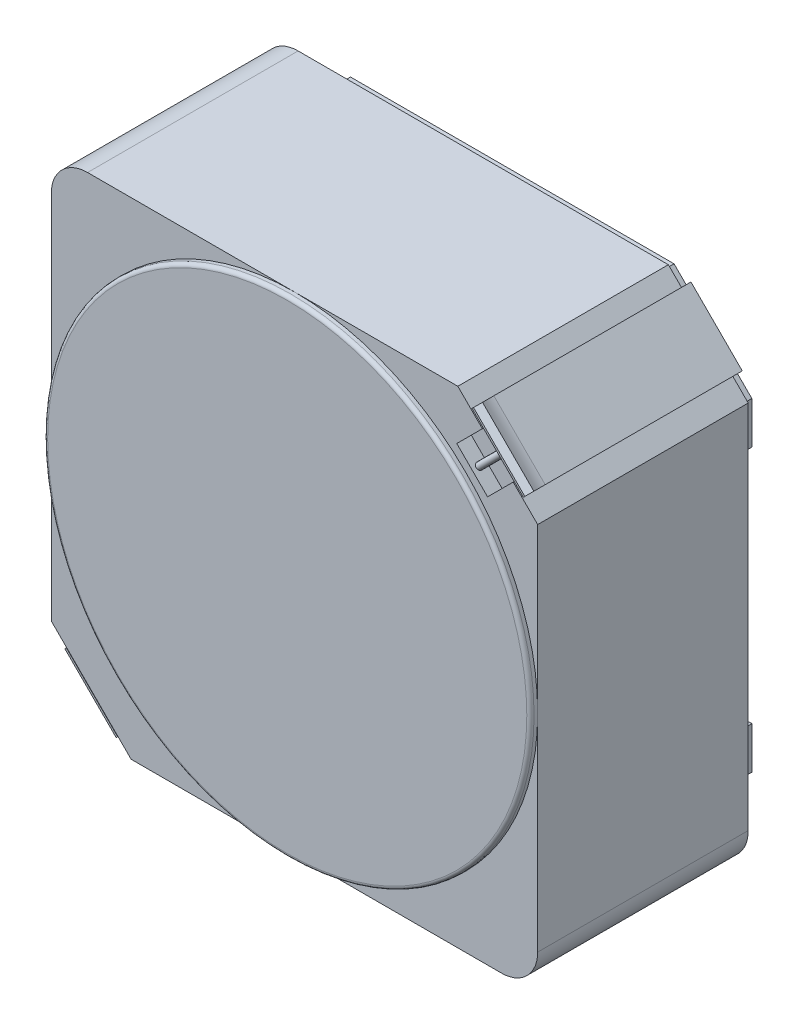
SolidWorks part; units mm, degrees
ref_plane "Спереди" through (0, 0, 0) normal (0, 0, 1) x (1, 0, 0)
ref_plane "Сверху" through (0, 0, 0) normal (0, 1, 0) x (1, 0, 0)
ref_plane "Справа" through (0, 0, 0) normal (1, 0, 0) x (0, 0, -1)
sketch "Эскиз1" plane through (0, 0, 0) normal (0, 0, 1) x (1, 0, 0)
  line L0 (-3.35, -2.25) -> (-2.25, -3.35)
  line L1 (-2.85, 3.35) -> (2.25, 3.35)
  line L2 (-3.35, 2.85) -> (-3.35, -2.25)
  line L3 (-2.25, -3.35) -> (2.85, -3.35)
  line L4 (3.35, 2.25) -> (3.35, -2.85)
  line L5 (-3.35, 3.35) -> (3.35, -3.35) construction
  line L6 (-3.35, -3.35) -> (3.35, 3.35) construction
  line L7 (2.25, 3.35) -> (3.35, 2.25)
  arc A0 (-2.85, 3.35) -> (-3.35, 2.85) centre (-2.85, 2.85) ccw
  arc A1 (2.85, -3.35) -> (3.35, -2.85) centre (2.85, -2.85) ccw
  point P0 (0, 0)
  dimension "D1" = 0.5
  dimension "D2" = 6.7
extrude "Корпус" add sketch "Эскиз1" along normal blind 2.9 from offset 0.1
sketch "Эскиз2" plane through (0, 0, 3) normal (0, 0, 1) x (1, 0, 0)
  line L0 (-3.35, 2.85) -> (-3.35, -2.25) construction
  circle A0 centre (0, 0) radius 3.35
extrude "Сердечник" add sketch "Эскиз2" along normal blind 0.1 and the other way blind 1
fillet "Скругление1" radius 0.05 1 edges at (3.35, 0, 3.1)
ref_plane "Плоскость1" through (0.55, -0.55, 0) normal (0.7071, -0.7071, 0) x (0, 0, 1)
sketch "Эскиз6" plane through (0.55, -0.55, 0) normal (0.7071, -0.7071, 0) x (0, 0, 1)
  line L0 (2.908, -4.0548) -> (2.995, -4.0028)
  line L1 (2.995, -3.9728) -> (0.125, -3.9728)
  line L2 (2.715, -4.0028) -> (0, -4.0028)
  line L3 (0, -4.0028) -> (0, -3.4728)
  line L4 (0.125, -3.9728) -> (0.125, -3.4728)
  line L5 (0.125, -3.4728) -> (0, -3.4728)
  line L6 (2.995, -4.0028) -> (2.995, -3.9728)
  line L8 (0.1, -3.9598) -> (3, -3.9598) construction
  line L9 (3, -3.35) -> (3, -2.3688) construction
  line L11 (0.1, 0.3536) -> (0.1, 3.9598) construction
  line L12 (3, -3.9598) -> (0.1, -3.9598) construction
  spline S0 degree 2 poles (2.715, -4.0028) (2.8188, -4.0066) (2.908, -4.0548) knots 0 0 0 1 1 1
  dimension "D2" = 0.5
  dimension "D3" = 0.013
  dimension "D4" = 0.025
  dimension "D5" = 0.005
  dimension "D6" = 0.082
  dimension "D7" = 0.087
  dimension "D8" = 120.867
  dimension "D9" = 0.28
  dimension "D10" = 0.1354
  dimension "D11" = 0.0295
  dimension "D12" = 0.03
extrude "вывод, бок" add sketch "Эскиз6" against normal blind 1 from offset 0.3 offset against normal yes
ref_point "Точка1"
ref_axis "Ось1" through (0, 0, 3.1) along (0, 0, -1)
sketch "Эскиз8" plane through (0, 0, 3) normal (0, 0, 1) x (1, 0, 0)
  line L0 (3.0121, 2.5879) -> (2.5879, 3.0121)
  line L2 (2.5879, 3.0121) -> (2.2357, 2.66)
  line L3 (-1.6879, -2.1121) -> (-1.3487, -1.7475)
  line L4 (2.4479, 2.4479) -> (0, 0) construction
  line L5 (3.0121, 2.5879) -> (2.66, 2.2357)
  line L6 (2.66, 2.2357) -> (2.2357, 2.66)
  line L7 (-1.788, -1.3388) -> (-1.3487, -1.7475)
  line L8 (-2.1272, -1.7034) -> (-1.788, -1.3388)
  line L9 (-2.1272, -1.7034) -> (-1.6879, -2.1121)
  line L10 (3.35, 2.25) -> (2.25, 3.35) construction
  dimension "D2" = 0.498
  dimension "D4" = 0.6
  dimension "D1" = 2
extrude "Вытянуть8" cut sketch "Эскиз8" against normal blind 0.2
sketch "Эскиз9" plane through (2.8092, 2.8092, 0) normal (-0.7071, -0.7071, 0) x (0, 0, 1)
  line L1 (0, 0) -> (2.899, 0) construction
  line L2 (2.995, 0.5222) -> (2.995, -0.4778) construction
  circle A0 centre (2.899, 0) radius 0.046
  dimension "D1" = 0.092
  dimension "D2" = 0.096
extrude "Бобышка-Вытянуть1" add sketch "Эскиз9" along normal up to next (0.511 mm away) and the other way blind 0.05 draft 45 from offset 0.05
pattern_circular "Круговой массив3" count 2 over 360 about axis through (0, 0, 3.1) along (0, 0, -1) of "вывод, бок", "Бобышка-Вытянуть1"
sketch "Эскиз13" plane through (0, 0, 0.1) normal (0, 0, -1) x (-1, 0, 0)
  line L1 (-3.35, -2.85) -> (-3.35, 2.25) construction
  line L2 (0, -3.3) -> (0, 0) construction
  line L3 (3.35, 2.85) -> (3.35, -2.25) construction
  line L4 (2.4308, -3.1692) -> (2.25, -3.35) construction
  line L5 (55, 0) -> (-55, 0) construction
  line L6 (2.3246, 1.6488) -> (3.3, 1.6488)
  line L7 (2.25, -3.35) -> (-2.85, -3.35) construction
  line L8 (3.3, 1.6488) -> (3.3, 2.2288)
  line L9 (2.2288, 3.3) -> (3.3, 2.2288)
  line L10 (-2.2288, 3.3) -> (2.2288, 3.3)
  line L11 (-3.3, 2.2288) -> (-2.2288, 3.3)
  line L12 (-3.3, -1.6488) -> (-2.3246, -1.6488)
  line L13 (-3.3, -2.2288) -> (-3.3, -1.6488)
  line L16 (-3.3, -2.2288) -> (-2.2288, -3.3)
  line L17 (-3.3, 2.2288) -> (-3.3, 1.6488)
  line L18 (-2.2288, -3.3) -> (2.2288, -3.3)
  line L19 (2.2288, -3.3) -> (3.3, -2.2288)
  line L20 (3.3, -1.6488) -> (3.3, -2.2288)
  line L21 (2.3246, -1.6488) -> (3.3, -1.6488)
  line L22 (-3.3, 1.6488) -> (-2.3246, 1.6488)
  arc A0 (-2.3246, -1.6488) -> (2.3246, -1.6488) centre (0, 0) ccw
  arc A1 (-2.3246, 1.6488) -> (2.3246, 1.6488) centre (0, 0) cw
  circle A2 centre (0, 0) radius 3.35 construction
  dimension "D2" = 0.5
  dimension "D3" = 0.9754
  dimension "D5" = 0.05
  dimension "D6" = 0.0503
  dimension "D7" = 0.05
  dimension "D1" = 0.58
extrude "Выводы низ" add sketch "Эскиз13" along normal up to surface (0.1 mm away) up to face at (-2.6273, -2.6587, 0)
